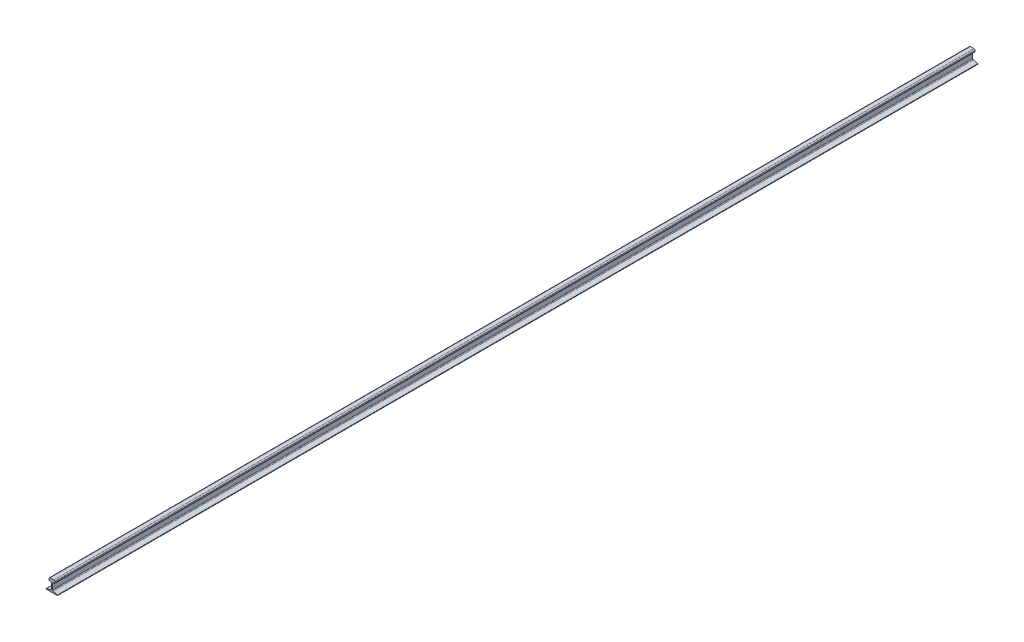
SolidWorks part; units mm, degrees
ref_plane "前视基准面" through (0, 0, 0) normal (0, 0, 1) x (1, 0, 0)
ref_plane "上视基准面" through (0, 0, 0) normal (0, 1, 0) x (1, 0, 0)
ref_plane "右视基准面" through (0, 0, 0) normal (1, 0, 0) x (0, 0, -1)
sketch "草图1" plane through (0, 0, 0) normal (0, 0, 1) x (1, 0, 0)
  line L0 (-9.7, 31.75) -> (9.7, 31.75)
  line L1 (6.6392, -22.9828) -> (0, -21.45) construction
  line L2 (6.6392, 16.416) -> (0, 14.27) construction
  line L3 (0, 0) -> (0, -31.75) construction
  line L8 (16.05, 25.4) -> (16.05, 19.8533)
  line L9 (14.8177, 18.3041) -> (6.6392, 16.416)
  line L17 (2.95, 11.778) -> (2.95, -18.3448)
  line L25 (6.6392, -22.9828) -> (30.5177, -28.4956)
  line L33 (31.75, -30.0448) -> (31.75, -30.16)
  line L34 (30.16, -31.75) -> (-30.16, -31.75)
  line L35 (-31.75, -30.16) -> (-31.75, -30.0448)
  line L43 (-30.5177, -28.4956) -> (-6.6392, -22.9828)
  line L51 (-2.95, -18.3448) -> (-2.95, 11.778)
  line L59 (-6.6392, 16.416) -> (-14.8177, 18.3041)
  line L60 (-16.05, 19.8533) -> (-16.05, 25.4)
  line L68 (0, 31.75) -> (0, -31.75) construction
  arc A0 (-16.05, 25.4) -> (-9.7, 31.75) centre (-9.7, 25.4) cw
  arc A1 (16.05, 25.4) -> (9.7, 31.75) centre (9.7, 25.4) ccw
  arc A2 (-6.6392, -22.9828) -> (-2.95, -18.3448) centre (-7.71, -18.3448) ccw
  arc A3 (6.6392, -22.9828) -> (2.95, -18.3448) centre (7.71, -18.3448) cw
  arc A4 (-31.75, -30.0448) -> (-30.5177, -28.4956) centre (-30.16, -30.0448) cw
  arc A5 (31.75, -30.0448) -> (30.5177, -28.4956) centre (30.16, -30.0448) ccw
  arc A6 (-2.95, 11.778) -> (-6.6392, 16.416) centre (-7.71, 11.778) ccw
  arc A7 (6.6392, 16.416) -> (2.95, 11.778) centre (7.71, 11.778) ccw
  arc A8 (-30.16, -31.75) -> (-31.75, -30.16) centre (-30.16, -30.16) cw
  arc A9 (31.75, -30.16) -> (30.16, -31.75) centre (30.16, -30.16) cw
  arc A10 (-14.8177, 18.3041) -> (-16.05, 19.8533) centre (-14.46, 19.8533) cw
  arc A11 (16.05, 19.8533) -> (14.8177, 18.3041) centre (14.46, 19.8533) cw
  point P13 (2.95, -22.1311)
  point P27 (2.95, 15.5642)
  point P31 (-31.75, -31.75)
  point P36 (31.75, -31.75)
  dimension "R1" = 6.35
  dimension "D7" = 4.76
  dimension "D12" = 1.59
  dimension "R2" = 4.76
  dimension "R3" = 1.59
  dimension "A" = 63.5
  dimension "T" = 5.9
  dimension "B" = 63.5
  dimension "D5" = 13
  dimension "C" = 32.1
  dimension "D10" = 77
  dimension "F" = 10.3
  dimension "E" = 35.72
  dimension "D8" = 31.75
extrude "拉伸1" add sketch "草图1" along normal mid plane 5000
equation "\"D7@草图1\" = \"R2@草图1\""
equation "\"D12@草图1\" = \"R3@草图1\""
equation "\"D8@草图1\" = \"A@草图1\"/2"
